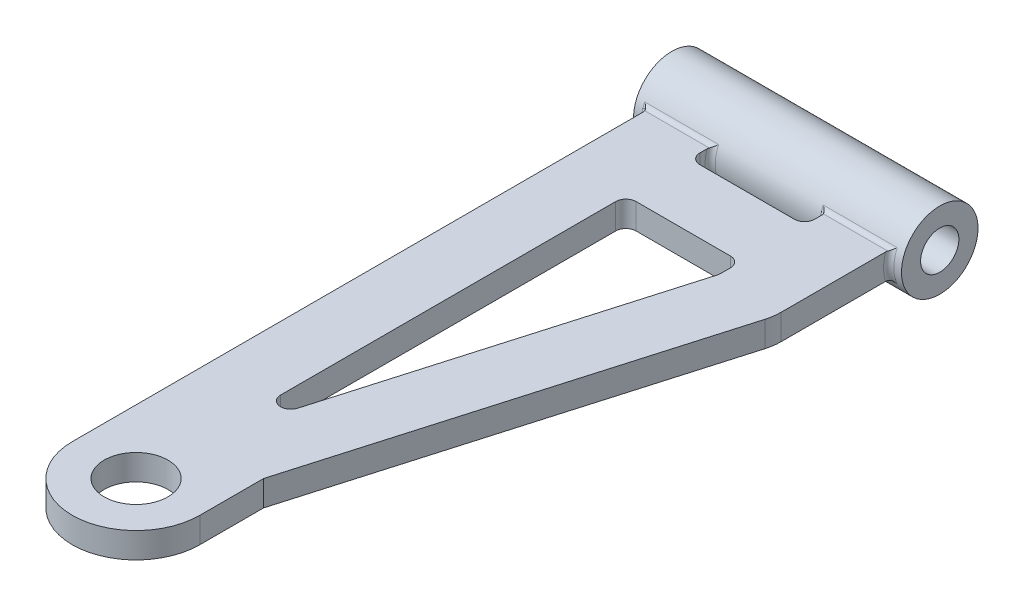
SolidWorks part; units mm, degrees
ref_plane "정면" through (0, 0, 0) normal (0, 0, 1) x (1, 0, 0)
ref_plane "윗면" through (0, 0, 0) normal (0, 1, 0) x (1, 0, 0)
ref_plane "우측면" through (0, 0, 0) normal (1, 0, 0) x (0, 0, -1)
sketch "스케치1" plane through (0, 0, 0) normal (1, 0, 0) x (0, 0, -1)
  circle A0 centre (0, 0) radius 15
  circle A1 centre (0, 0) radius 7.5
  dimension "D1" = 30
  dimension "D2" = 15
extrude "보스-돌출1" add sketch "스케치1" along normal mid plane 105
sketch "스케치2" plane through (0, 0, 0) normal (0, 1, 0) x (1, 0, 0)
  line L0 (-47.5, -12) -> (-47.5, -240)
  line L2 (-47.5, -240) -> (2.5, -240) construction
  line L3 (2.5, -240) -> (2.5, -215)
  line L4 (2.5, -215) -> (47.5, -60)
  line L5 (47.5, -60) -> (47.5, -12)
  line L7 (-52.5, 0) -> (52.5, 0) construction
  line L8 (-52.5, 15) -> (-52.5, -15) construction
  line L9 (52.5, -15) -> (52.5, 15) construction
  line L10 (-52.5, -15) -> (52.5, -15) construction
  line L11 (-22.5, -12) -> (-22.5, -23)
  line L12 (-14.6586, -184.4352) -> (22.5, -56.4444)
  line L13 (22.5, -56.4444) -> (22.5, -48)
  line L14 (-47.5, -12) -> (-22.5, -12)
  line L15 (22.5, -60) -> (22.5, 0) construction
  line L16 (-21.5087, -208.0297) -> (23.4913, -53.0297) construction
  line L17 (-22.5, -23) -> (22.5, -23)
  line L18 (-22.5, 0) -> (-22.5, -240) construction
  line L19 (-22.5, -48) -> (22.5, -48)
  line L20 (-52.5, -15) -> (52.5, -15) construction
  line L21 (-22.5, -48) -> (-22.5, -183.3199)
  line L22 (-47.5, 0) -> (-47.5, -240) construction
  line L23 (47.5, -60) -> (47.5, 0) construction
  line L24 (22.5, -23) -> (22.5, -12)
  line L25 (22.5, -12) -> (47.5, -12)
  line L26 (-52.5, -15) -> (52.5, -15) construction
  arc A0 (-47.5, -240) -> (2.5, -240) centre (-22.5, -240) ccw
  arc A1 (-22.5, -183.3199) -> (-14.6586, -184.4352) centre (-18.5, -183.3199) ccw
  circle A2 centre (-22.5, -240) radius 12.5
  dimension "D5" = 50
  dimension "D10" = 8
  dimension "D2" = 25
  dimension "D3" = 45
  dimension "D4" = 240
  dimension "D6" = 25
  dimension "D11" = 25
  dimension "D12" = 3
  dimension "D13" = 8
  dimension "D14" = 95
  dimension "D15" = 47.5
  dimension "D7" = 25
  dimension "D8" = 25
  dimension "D9" = 25
extrude "보스-돌출2" add sketch "스케치2" along normal mid plane 10
fillet "필렛1" radius 4 5 edges at (22.5, 0, 23) (-22.5, 0, 23) (22.5, 0, 56.4444) (22.5, 0, 48) (-22.5, 0, 48)
fillet "필렛2" radius 20 1 edges at (47.5, 0, 60)
fillet "필렛3" radius 2 8 edges at (22.5, 0, 15) (-22.5, 0, 15) (-35, -5, 14.1421) (-47.5, 0, 15) (35, -5, 14.1421) (47.5, 0, 15) (35, 5, 14.1421) (-35, 5, 14.1421)
